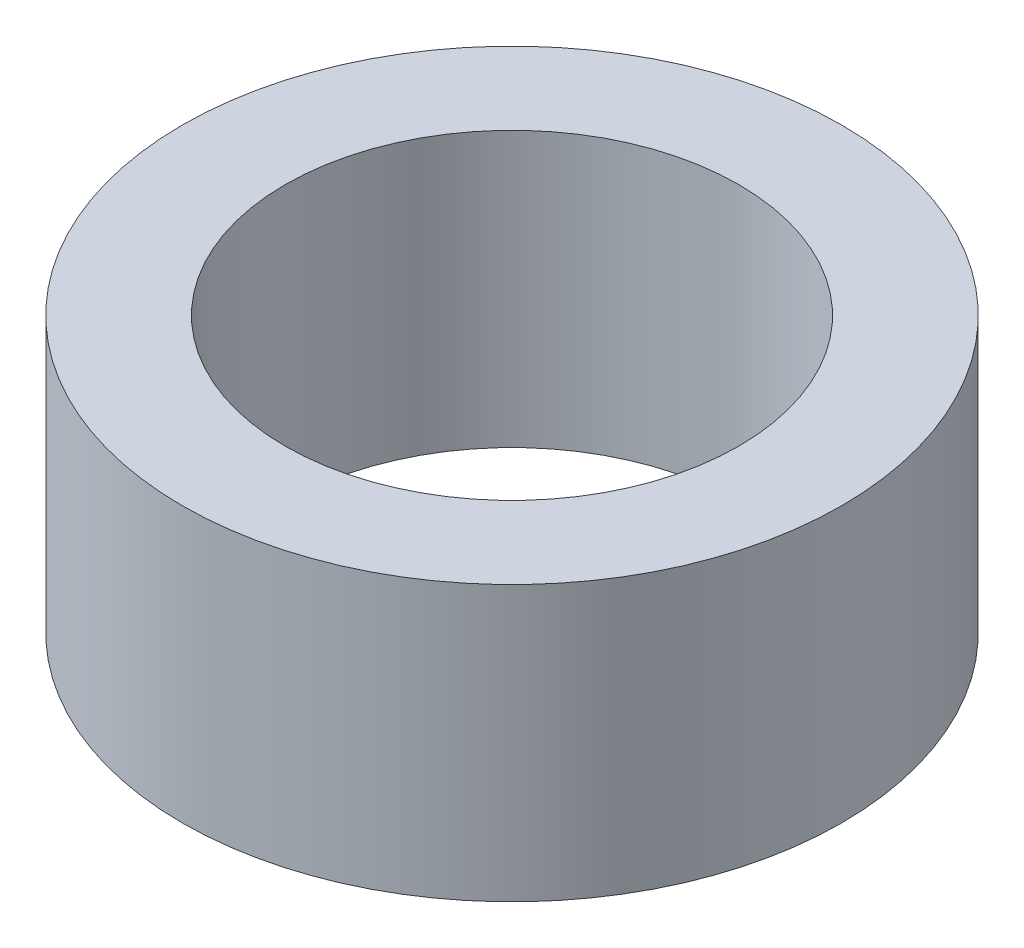
SolidWorks part; units mm, degrees
ref_plane "前视基准面" through (0, 0, 0) normal (0, 0, 1) x (1, 0, 0)
ref_plane "上视基准面" through (0, 0, 0) normal (0, 1, 0) x (1, 0, 0)
ref_plane "右视基准面" through (0, 0, 0) normal (1, 0, 0) x (0, 0, -1)
sketch "草图1" plane through (0, 0, 0) normal (0, 1, 0) x (1, 0, 0)
  circle A0 centre (0, 0) radius 1.65
  circle A1 centre (0, 0) radius 2.4
  dimension "D1" = 3.3
  dimension "D2" = 4.8
extrude "凸台-拉伸1" add sketch "草图1" along normal blind 2
